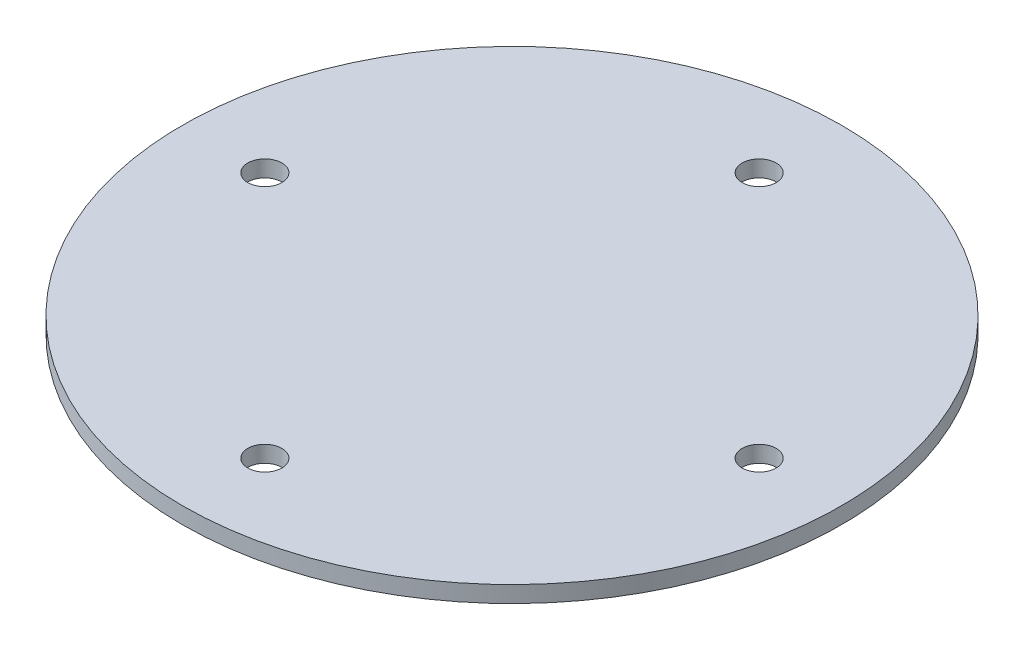
SolidWorks part; units mm, degrees
ref_plane "Front Plane" through (0, 0, 0) normal (0, 0, 1) x (1, 0, 0)
ref_plane "Top Plane" through (0, 0, 0) normal (0, 1, 0) x (1, 0, 0)
ref_plane "Right Plane" through (0, 0, 0) normal (1, 0, 0) x (0, 0, -1)
sketch "Sketch1" plane through (0, 0, 0) normal (0, 1, 0) x (1, 0, 0)
  circle A0 centre (0, 0) radius 60
  circle A1 centre (0, 0) radius 45 construction
  circle A2 centre (-45, 0) radius 3.1
  circle A3 centre (0, 45) radius 3.1
  circle A4 centre (45, 0) radius 3.1
  circle A5 centre (0, -45) radius 3.1
  dimension "D1" = 120
  dimension "D2" = 90
  dimension "D3" = 6.2
  dimension "D4" = 4
extrude "Boss-Extrude1" add sketch "Sketch1" along normal blind 3
